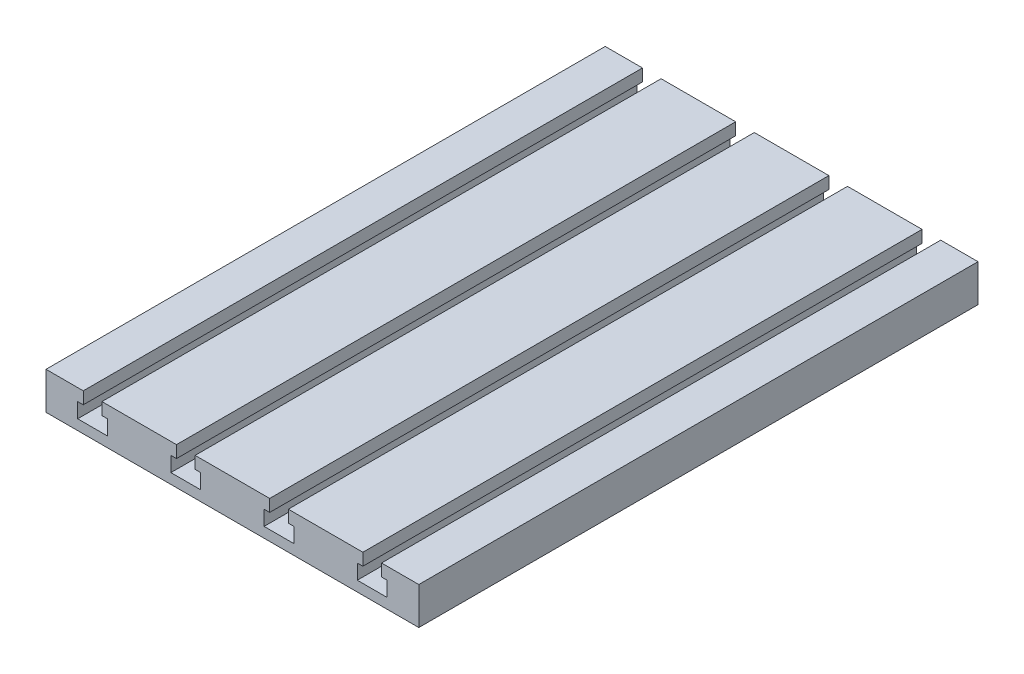
SolidWorks part; units mm, degrees
ref_plane "Ebene vorne" through (0, 0, 0) normal (0, 0, 1) x (1, 0, 0)
ref_plane "Ebene oben" through (0, 0, 0) normal (0, 1, 0) x (1, 0, 0)
ref_plane "Ebene rechts" through (0, 0, 0) normal (1, 0, 0) x (0, 0, -1)
sketch "Skizze1" plane through (0, 0, 0) normal (0, 0, 1) x (1, 0, 0)
  line L0 (0, 0) -> (0, 20)
  line L1 (0, 20) -> (20, 20)
  line L2 (20, 20) -> (20, 13.5)
  line L3 (20, 13.5) -> (17, 13.5)
  line L4 (17, 13.5) -> (17, 5.5)
  line L5 (17, 5.5) -> (33, 5.5)
  line L6 (33, 5.5) -> (33, 13.5)
  line L7 (33, 13.5) -> (30, 13.5)
  line L8 (30, 13.5) -> (30, 20)
  line L9 (30, 20) -> (70, 20)
  line L10 (70, 20) -> (70, 13.5)
  line L11 (70, 13.5) -> (67, 13.5)
  line L12 (67, 13.5) -> (67, 5.5)
  line L13 (67, 5.5) -> (83, 5.5)
  line L14 (83, 5.5) -> (83, 13.5)
  line L15 (83, 13.5) -> (80, 13.5)
  line L16 (80, 13.5) -> (80, 20)
  line L17 (80, 20) -> (120, 20)
  line L18 (120, 20) -> (120, 13.5)
  line L19 (120, 13.5) -> (117, 13.5)
  line L20 (117, 13.5) -> (117, 5.5)
  line L21 (117, 5.5) -> (133, 5.5)
  line L22 (133, 5.5) -> (133, 13.5)
  line L23 (133, 13.5) -> (130, 13.5)
  line L24 (130, 13.5) -> (130, 20)
  line L25 (130, 20) -> (170, 20)
  line L26 (170, 20) -> (170, 13.5)
  line L27 (170, 13.5) -> (167, 13.5)
  line L28 (167, 13.5) -> (167, 5.5)
  line L29 (167, 5.5) -> (183, 5.5)
  line L30 (183, 5.5) -> (183, 13.5)
  line L31 (183, 13.5) -> (180, 13.5)
  line L32 (180, 13.5) -> (180, 20)
  line L33 (180, 20) -> (200, 20)
  line L34 (200, 20) -> (200, 0)
  line L35 (200, 0) -> (0, 0)
  dimension "D1" = 20
  dimension "D2" = 200
  dimension "D3" = 20
  dimension "D4" = 40
  dimension "D5" = 40
  dimension "D6" = 40
  dimension "D7" = 20
  dimension "D8" = 10
  dimension "D9" = 10
  dimension "D10" = 10
  dimension "D11" = 6.5
  dimension "D12" = 6.5
  dimension "D13" = 6.5
  dimension "D14" = 6.5
  dimension "D15" = 16
  dimension "D16" = 3
  dimension "D17" = 3
  dimension "D18" = 3
  dimension "D19" = 3
  dimension "D20" = 16
  dimension "D21" = 16
  dimension "D22" = 16
  dimension "D23" = 8
  dimension "D24" = 8
  dimension "D25" = 8
  dimension "D26" = 8
  dimension "D27" = 20
  dimension "D28" = 20
  dimension "D29" = 20
  dimension "D30" = 6.5
extrude "Aufsatz-Linear austragen1" add sketch "Skizze1" along normal blind 300
